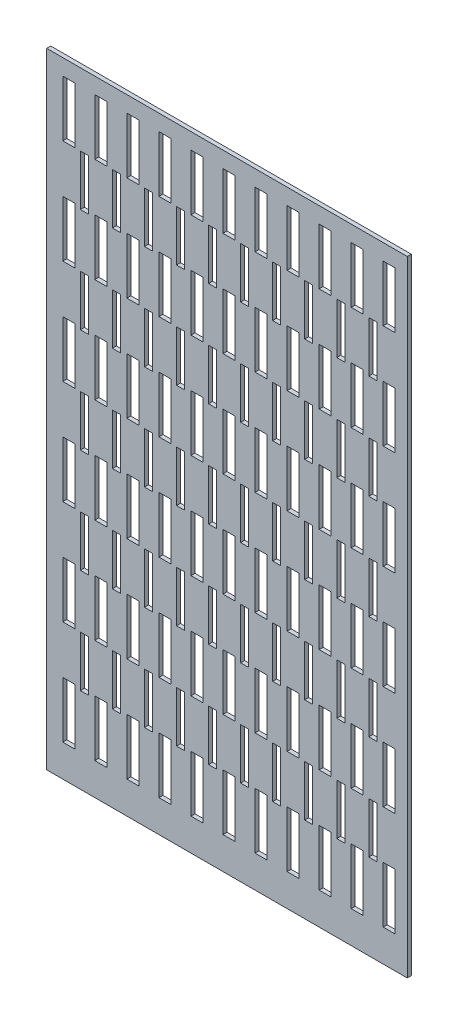
SolidWorks part; units mm, degrees
ref_plane "前视基准面" through (0, 0, 0) normal (0, 0, 1) x (1, 0, 0)
ref_plane "上视基准面" through (0, 0, 0) normal (0, 1, 0) x (1, 0, 0)
ref_plane "右视基准面" through (0, 0, 0) normal (1, 0, 0) x (0, 0, -1)
sketch "草图1" plane through (0, 0, 0) normal (0, 0, 1) x (1, 0, 0)
  line L1 (-22.5, 78) -> (22.5, 78)
  line L2 (-22.5, 78) -> (-22.5, 0)
  line L3 (-22.5, 0) -> (22.5, 0)
  line L4 (22.5, 78) -> (22.5, 0)
  dimension "D1" = 45
  dimension "D2" = 78
  dimension "D3" = 22.5
extrude "凸台-拉伸1" add sketch "草图1" along normal blind 0.5
sketch "草图2" plane through (0, 0, 0.5) normal (0, 0, 1) x (1, 0, 0)
  line L0 (-22.5, 78) -> (-22.5, 0) construction
  line L1 (-20.5, 76) -> (-19, 76)
  line L2 (-20.5, 76) -> (-20.5, 69)
  line L3 (-20.5, 69) -> (-19, 69)
  line L4 (-19, 76) -> (-19, 69)
  line L5 (22.5, 78) -> (-22.5, 78) construction
  line L6 (-16.5, 76) -> (-16.5, 69)
  line L7 (-16.5, 76) -> (-15, 76)
  line L8 (-15, 76) -> (-15, 69)
  line L9 (-16.5, 69) -> (-15, 69)
  line L10 (-12.5, 76) -> (-12.5, 69)
  line L11 (-12.5, 76) -> (-11, 76)
  line L12 (-11, 76) -> (-11, 69)
  line L13 (-12.5, 69) -> (-11, 69)
  line L14 (-8.5, 76) -> (-8.5, 69)
  line L15 (-8.5, 76) -> (-7, 76)
  line L16 (-7, 76) -> (-7, 69)
  line L17 (-8.5, 69) -> (-7, 69)
  line L18 (-4.5, 76) -> (-4.5, 69)
  line L19 (-4.5, 76) -> (-3, 76)
  line L20 (-3, 76) -> (-3, 69)
  line L21 (-4.5, 69) -> (-3, 69)
  line L22 (-0.5, 76) -> (-0.5, 69)
  line L23 (-0.5, 76) -> (1, 76)
  line L24 (1, 76) -> (1, 69)
  line L25 (-0.5, 69) -> (1, 69)
  line L26 (3.5, 76) -> (3.5, 69)
  line L27 (3.5, 76) -> (5, 76)
  line L28 (5, 76) -> (5, 69)
  line L29 (3.5, 69) -> (5, 69)
  line L30 (7.5, 76) -> (7.5, 69)
  line L31 (7.5, 76) -> (9, 76)
  line L32 (9, 76) -> (9, 69)
  line L33 (7.5, 69) -> (9, 69)
  line L34 (11.5, 76) -> (11.5, 69)
  line L35 (11.5, 76) -> (13, 76)
  line L36 (13, 76) -> (13, 69)
  line L37 (11.5, 69) -> (13, 69)
  line L38 (15.5, 76) -> (15.5, 69)
  line L39 (15.5, 76) -> (17, 76)
  line L40 (17, 76) -> (17, 69)
  line L41 (15.5, 69) -> (17, 69)
  line L42 (19.5, 76) -> (19.5, 69)
  line L43 (19.5, 76) -> (21, 76)
  line L44 (21, 76) -> (21, 69)
  line L45 (19.5, 69) -> (21, 69)
  line L46 (-20.5, 63) -> (-20.5, 56)
  line L47 (-20.5, 63) -> (-19, 63)
  line L48 (-19, 63) -> (-19, 56)
  line L49 (-20.5, 56) -> (-19, 56)
  line L50 (-16.5, 63) -> (-16.5, 56)
  line L51 (-16.5, 56) -> (-15, 56)
  line L52 (-15, 63) -> (-15, 56)
  line L53 (-16.5, 63) -> (-15, 63)
  line L54 (-12.5, 63) -> (-12.5, 56)
  line L55 (-12.5, 56) -> (-11, 56)
  line L56 (-11, 63) -> (-11, 56)
  line L57 (-12.5, 63) -> (-11, 63)
  line L58 (-8.5, 63) -> (-8.5, 56)
  line L59 (-8.5, 56) -> (-7, 56)
  line L60 (-7, 63) -> (-7, 56)
  line L61 (-8.5, 63) -> (-7, 63)
  line L62 (-4.5, 63) -> (-4.5, 56)
  line L63 (-4.5, 56) -> (-3, 56)
  line L64 (-3, 63) -> (-3, 56)
  line L65 (-4.5, 63) -> (-3, 63)
  line L66 (-0.5, 63) -> (-0.5, 56)
  line L67 (-0.5, 56) -> (1, 56)
  line L68 (1, 63) -> (1, 56)
  line L69 (-0.5, 63) -> (1, 63)
  line L70 (3.5, 63) -> (3.5, 56)
  line L71 (3.5, 56) -> (5, 56)
  line L72 (5, 63) -> (5, 56)
  line L73 (3.5, 63) -> (5, 63)
  line L74 (7.5, 63) -> (7.5, 56)
  line L75 (7.5, 56) -> (9, 56)
  line L76 (9, 63) -> (9, 56)
  line L77 (7.5, 63) -> (9, 63)
  line L78 (11.5, 63) -> (11.5, 56)
  line L79 (11.5, 56) -> (13, 56)
  line L80 (13, 63) -> (13, 56)
  line L81 (11.5, 63) -> (13, 63)
  line L82 (15.5, 63) -> (15.5, 56)
  line L83 (15.5, 56) -> (17, 56)
  line L84 (17, 63) -> (17, 56)
  line L85 (15.5, 63) -> (17, 63)
  line L86 (19.5, 63) -> (19.5, 56)
  line L87 (19.5, 56) -> (21, 56)
  line L88 (21, 63) -> (21, 56)
  line L89 (19.5, 63) -> (21, 63)
  line L90 (-20.5, 50) -> (-20.5, 43)
  line L91 (-20.5, 50) -> (-19, 50)
  line L92 (-19, 50) -> (-19, 43)
  line L93 (-20.5, 43) -> (-19, 43)
  line L94 (-16.5, 50) -> (-16.5, 43)
  line L95 (-16.5, 43) -> (-15, 43)
  line L96 (-15, 50) -> (-15, 43)
  line L97 (-16.5, 50) -> (-15, 50)
  line L98 (-12.5, 50) -> (-12.5, 43)
  line L99 (-12.5, 43) -> (-11, 43)
  line L100 (-11, 50) -> (-11, 43)
  line L101 (-12.5, 50) -> (-11, 50)
  line L102 (-8.5, 50) -> (-8.5, 43)
  line L103 (-8.5, 43) -> (-7, 43)
  line L104 (-7, 50) -> (-7, 43)
  line L105 (-8.5, 50) -> (-7, 50)
  line L106 (-4.5, 50) -> (-4.5, 43)
  line L107 (-4.5, 43) -> (-3, 43)
  line L108 (-3, 50) -> (-3, 43)
  line L109 (-4.5, 50) -> (-3, 50)
  line L110 (-0.5, 50) -> (-0.5, 43)
  line L111 (-0.5, 43) -> (1, 43)
  line L112 (1, 50) -> (1, 43)
  line L113 (-0.5, 50) -> (1, 50)
  line L114 (3.5, 50) -> (3.5, 43)
  line L115 (3.5, 43) -> (5, 43)
  line L116 (5, 50) -> (5, 43)
  line L117 (3.5, 50) -> (5, 50)
  line L118 (7.5, 50) -> (7.5, 43)
  line L119 (7.5, 43) -> (9, 43)
  line L120 (9, 50) -> (9, 43)
  line L121 (7.5, 50) -> (9, 50)
  line L122 (11.5, 50) -> (11.5, 43)
  line L123 (11.5, 43) -> (13, 43)
  line L124 (13, 50) -> (13, 43)
  line L125 (11.5, 50) -> (13, 50)
  line L126 (15.5, 50) -> (15.5, 43)
  line L127 (15.5, 43) -> (17, 43)
  line L128 (17, 50) -> (17, 43)
  line L129 (15.5, 50) -> (17, 50)
  line L130 (19.5, 50) -> (19.5, 43)
  line L131 (19.5, 43) -> (21, 43)
  line L132 (21, 50) -> (21, 43)
  line L133 (19.5, 50) -> (21, 50)
  line L134 (-20.5, 37) -> (-20.5, 30)
  line L135 (-20.5, 37) -> (-19, 37)
  line L136 (-19, 37) -> (-19, 30)
  line L137 (-20.5, 30) -> (-19, 30)
  line L138 (-16.5, 37) -> (-16.5, 30)
  line L139 (-16.5, 30) -> (-15, 30)
  line L140 (-15, 37) -> (-15, 30)
  line L141 (-16.5, 37) -> (-15, 37)
  line L142 (-12.5, 37) -> (-12.5, 30)
  line L143 (-12.5, 30) -> (-11, 30)
  line L144 (-11, 37) -> (-11, 30)
  line L145 (-12.5, 37) -> (-11, 37)
  line L146 (-8.5, 37) -> (-8.5, 30)
  line L147 (-8.5, 30) -> (-7, 30)
  line L148 (-7, 37) -> (-7, 30)
  line L149 (-8.5, 37) -> (-7, 37)
  line L150 (-4.5, 37) -> (-4.5, 30)
  line L151 (-4.5, 30) -> (-3, 30)
  line L152 (-3, 37) -> (-3, 30)
  line L153 (-4.5, 37) -> (-3, 37)
  line L154 (-0.5, 37) -> (-0.5, 30)
  line L155 (-0.5, 30) -> (1, 30)
  line L156 (1, 37) -> (1, 30)
  line L157 (-0.5, 37) -> (1, 37)
  line L158 (3.5, 37) -> (3.5, 30)
  line L159 (3.5, 30) -> (5, 30)
  line L160 (5, 37) -> (5, 30)
  line L161 (3.5, 37) -> (5, 37)
  line L162 (7.5, 37) -> (7.5, 30)
  line L163 (7.5, 30) -> (9, 30)
  line L164 (9, 37) -> (9, 30)
  line L165 (7.5, 37) -> (9, 37)
  line L166 (11.5, 37) -> (11.5, 30)
  line L167 (11.5, 30) -> (13, 30)
  line L168 (13, 37) -> (13, 30)
  line L169 (11.5, 37) -> (13, 37)
  line L170 (15.5, 37) -> (15.5, 30)
  line L171 (15.5, 30) -> (17, 30)
  line L172 (17, 37) -> (17, 30)
  line L173 (15.5, 37) -> (17, 37)
  line L174 (19.5, 37) -> (19.5, 30)
  line L175 (19.5, 30) -> (21, 30)
  line L176 (21, 37) -> (21, 30)
  line L177 (19.5, 37) -> (21, 37)
  line L178 (-20.5, 24) -> (-20.5, 17)
  line L179 (-20.5, 24) -> (-19, 24)
  line L180 (-19, 24) -> (-19, 17)
  line L181 (-20.5, 17) -> (-19, 17)
  line L182 (-16.5, 24) -> (-16.5, 17)
  line L183 (-16.5, 17) -> (-15, 17)
  line L184 (-15, 24) -> (-15, 17)
  line L185 (-16.5, 24) -> (-15, 24)
  line L186 (-12.5, 24) -> (-12.5, 17)
  line L187 (-12.5, 17) -> (-11, 17)
  line L188 (-11, 24) -> (-11, 17)
  line L189 (-12.5, 24) -> (-11, 24)
  line L190 (-8.5, 24) -> (-8.5, 17)
  line L191 (-8.5, 17) -> (-7, 17)
  line L192 (-7, 24) -> (-7, 17)
  line L193 (-8.5, 24) -> (-7, 24)
  line L194 (-4.5, 24) -> (-4.5, 17)
  line L195 (-4.5, 17) -> (-3, 17)
  line L196 (-3, 24) -> (-3, 17)
  line L197 (-4.5, 24) -> (-3, 24)
  line L198 (-0.5, 24) -> (-0.5, 17)
  line L199 (-0.5, 17) -> (1, 17)
  line L200 (1, 24) -> (1, 17)
  line L201 (-0.5, 24) -> (1, 24)
  line L202 (3.5, 24) -> (3.5, 17)
  line L203 (3.5, 17) -> (5, 17)
  line L204 (5, 24) -> (5, 17)
  line L205 (3.5, 24) -> (5, 24)
  line L206 (7.5, 24) -> (7.5, 17)
  line L207 (7.5, 17) -> (9, 17)
  line L208 (9, 24) -> (9, 17)
  line L209 (7.5, 24) -> (9, 24)
  line L210 (11.5, 24) -> (11.5, 17)
  line L211 (11.5, 17) -> (13, 17)
  line L212 (13, 24) -> (13, 17)
  line L213 (11.5, 24) -> (13, 24)
  line L214 (15.5, 24) -> (15.5, 17)
  line L215 (15.5, 17) -> (17, 17)
  line L216 (17, 24) -> (17, 17)
  line L217 (15.5, 24) -> (17, 24)
  line L218 (19.5, 24) -> (19.5, 17)
  line L219 (19.5, 17) -> (21, 17)
  line L220 (21, 24) -> (21, 17)
  line L221 (19.5, 24) -> (21, 24)
  line L222 (-20.5, 11) -> (-20.5, 4)
  line L223 (-20.5, 11) -> (-19, 11)
  line L224 (-19, 11) -> (-19, 4)
  line L225 (-20.5, 4) -> (-19, 4)
  line L226 (-16.5, 11) -> (-16.5, 4)
  line L227 (-16.5, 4) -> (-15, 4)
  line L228 (-15, 11) -> (-15, 4)
  line L229 (-16.5, 11) -> (-15, 11)
  line L230 (-12.5, 11) -> (-12.5, 4)
  line L231 (-12.5, 4) -> (-11, 4)
  line L232 (-11, 11) -> (-11, 4)
  line L233 (-12.5, 11) -> (-11, 11)
  line L234 (-8.5, 11) -> (-8.5, 4)
  line L235 (-8.5, 4) -> (-7, 4)
  line L236 (-7, 11) -> (-7, 4)
  line L237 (-8.5, 11) -> (-7, 11)
  line L238 (-4.5, 11) -> (-4.5, 4)
  line L239 (-4.5, 4) -> (-3, 4)
  line L240 (-3, 11) -> (-3, 4)
  line L241 (-4.5, 11) -> (-3, 11)
  line L242 (-0.5, 11) -> (-0.5, 4)
  line L243 (-0.5, 4) -> (1, 4)
  line L244 (1, 11) -> (1, 4)
  line L245 (-0.5, 11) -> (1, 11)
  line L246 (3.5, 11) -> (3.5, 4)
  line L247 (3.5, 4) -> (5, 4)
  line L248 (5, 11) -> (5, 4)
  line L249 (3.5, 11) -> (5, 11)
  line L250 (7.5, 11) -> (7.5, 4)
  line L251 (7.5, 4) -> (9, 4)
  line L252 (9, 11) -> (9, 4)
  line L253 (7.5, 11) -> (9, 11)
  line L254 (11.5, 11) -> (11.5, 4)
  line L255 (11.5, 4) -> (13, 4)
  line L256 (13, 11) -> (13, 4)
  line L257 (11.5, 11) -> (13, 11)
  line L258 (15.5, 11) -> (15.5, 4)
  line L259 (15.5, 4) -> (17, 4)
  line L260 (17, 11) -> (17, 4)
  line L261 (15.5, 11) -> (17, 11)
  line L262 (19.5, 11) -> (19.5, 4)
  line L263 (19.5, 4) -> (21, 4)
  line L264 (21, 11) -> (21, 4)
  line L265 (19.5, 11) -> (21, 11)
  line L266 (-14.3, 69) -> (-14.3, 62.6737)
  line L267 (-18.3, 69) -> (-17.3, 69)
  line L268 (-18.3, 69) -> (-18.3, 62.6737)
  line L269 (-18.3, 62.6737) -> (-17.3, 62.6737)
  line L270 (-17.3, 69) -> (-17.3, 62.6737)
  line L271 (-14.3, 69) -> (-13.3, 69)
  line L272 (-13.3, 69) -> (-13.3, 62.6737)
  line L273 (-14.3, 62.6737) -> (-13.3, 62.6737)
  line L274 (-10.3, 69) -> (-10.3, 62.6737)
  line L275 (-10.3, 69) -> (-9.3, 69)
  line L276 (-9.3, 69) -> (-9.3, 62.6737)
  line L277 (-10.3, 62.6737) -> (-9.3, 62.6737)
  line L278 (-6.3, 69) -> (-6.3, 62.6737)
  line L279 (-6.3, 69) -> (-5.3, 69)
  line L280 (-5.3, 69) -> (-5.3, 62.6737)
  line L281 (-6.3, 62.6737) -> (-5.3, 62.6737)
  line L282 (-2.3, 69) -> (-2.3, 62.6737)
  line L283 (-2.3, 69) -> (-1.3, 69)
  line L284 (-1.3, 69) -> (-1.3, 62.6737)
  line L285 (-2.3, 62.6737) -> (-1.3, 62.6737)
  line L286 (1.7, 69) -> (1.7, 62.6737)
  line L287 (1.7, 69) -> (2.7, 69)
  line L288 (2.7, 69) -> (2.7, 62.6737)
  line L289 (1.7, 62.6737) -> (2.7, 62.6737)
  line L290 (5.7, 69) -> (5.7, 62.6737)
  line L291 (5.7, 69) -> (6.7, 69)
  line L292 (6.7, 69) -> (6.7, 62.6737)
  line L293 (5.7, 62.6737) -> (6.7, 62.6737)
  line L294 (9.7, 69) -> (9.7, 62.6737)
  line L295 (9.7, 69) -> (10.7, 69)
  line L296 (10.7, 69) -> (10.7, 62.6737)
  line L297 (9.7, 62.6737) -> (10.7, 62.6737)
  line L298 (13.7, 69) -> (13.7, 62.6737)
  line L299 (13.7, 69) -> (14.7, 69)
  line L300 (14.7, 69) -> (14.7, 62.6737)
  line L301 (13.7, 62.6737) -> (14.7, 62.6737)
  line L302 (17.7, 69) -> (17.7, 62.6737)
  line L303 (17.7, 69) -> (18.7, 69)
  line L304 (18.7, 69) -> (18.7, 62.6737)
  line L305 (17.7, 62.6737) -> (18.7, 62.6737)
  line L306 (-18.3, 56) -> (-18.3, 49.6737)
  line L307 (-18.3, 56) -> (-17.3, 56)
  line L308 (-17.3, 56) -> (-17.3, 49.6737)
  line L309 (-18.3, 49.6737) -> (-17.3, 49.6737)
  line L310 (-14.3, 56) -> (-14.3, 49.6737)
  line L311 (-14.3, 49.6737) -> (-13.3, 49.6737)
  line L312 (-13.3, 56) -> (-13.3, 49.6737)
  line L313 (-14.3, 56) -> (-13.3, 56)
  line L314 (-10.3, 56) -> (-10.3, 49.6737)
  line L315 (-10.3, 49.6737) -> (-9.3, 49.6737)
  line L316 (-9.3, 56) -> (-9.3, 49.6737)
  line L317 (-10.3, 56) -> (-9.3, 56)
  line L318 (-6.3, 56) -> (-6.3, 49.6737)
  line L319 (-6.3, 49.6737) -> (-5.3, 49.6737)
  line L320 (-5.3, 56) -> (-5.3, 49.6737)
  line L321 (-6.3, 56) -> (-5.3, 56)
  line L322 (-2.3, 56) -> (-2.3, 49.6737)
  line L323 (-2.3, 49.6737) -> (-1.3, 49.6737)
  line L324 (-1.3, 56) -> (-1.3, 49.6737)
  line L325 (-2.3, 56) -> (-1.3, 56)
  line L326 (1.7, 56) -> (1.7, 49.6737)
  line L327 (1.7, 49.6737) -> (2.7, 49.6737)
  line L328 (2.7, 56) -> (2.7, 49.6737)
  line L329 (1.7, 56) -> (2.7, 56)
  line L330 (5.7, 56) -> (5.7, 49.6737)
  line L331 (5.7, 49.6737) -> (6.7, 49.6737)
  line L332 (6.7, 56) -> (6.7, 49.6737)
  line L333 (5.7, 56) -> (6.7, 56)
  line L334 (9.7, 56) -> (9.7, 49.6737)
  line L335 (9.7, 49.6737) -> (10.7, 49.6737)
  line L336 (10.7, 56) -> (10.7, 49.6737)
  line L337 (9.7, 56) -> (10.7, 56)
  line L338 (13.7, 56) -> (13.7, 49.6737)
  line L339 (13.7, 49.6737) -> (14.7, 49.6737)
  line L340 (14.7, 56) -> (14.7, 49.6737)
  line L341 (13.7, 56) -> (14.7, 56)
  line L342 (17.7, 56) -> (17.7, 49.6737)
  line L343 (17.7, 49.6737) -> (18.7, 49.6737)
  line L344 (18.7, 56) -> (18.7, 49.6737)
  line L345 (17.7, 56) -> (18.7, 56)
  line L346 (-18.3, 43) -> (-18.3, 36.6737)
  line L347 (-18.3, 43) -> (-17.3, 43)
  line L348 (-17.3, 43) -> (-17.3, 36.6737)
  line L349 (-18.3, 36.6737) -> (-17.3, 36.6737)
  line L350 (-14.3, 43) -> (-14.3, 36.6737)
  line L351 (-14.3, 36.6737) -> (-13.3, 36.6737)
  line L352 (-13.3, 43) -> (-13.3, 36.6737)
  line L353 (-14.3, 43) -> (-13.3, 43)
  line L354 (-10.3, 43) -> (-10.3, 36.6737)
  line L355 (-10.3, 36.6737) -> (-9.3, 36.6737)
  line L356 (-9.3, 43) -> (-9.3, 36.6737)
  line L357 (-10.3, 43) -> (-9.3, 43)
  line L358 (-6.3, 43) -> (-6.3, 36.6737)
  line L359 (-6.3, 36.6737) -> (-5.3, 36.6737)
  line L360 (-5.3, 43) -> (-5.3, 36.6737)
  line L361 (-6.3, 43) -> (-5.3, 43)
  line L362 (-2.3, 43) -> (-2.3, 36.6737)
  line L363 (-2.3, 36.6737) -> (-1.3, 36.6737)
  line L364 (-1.3, 43) -> (-1.3, 36.6737)
  line L365 (-2.3, 43) -> (-1.3, 43)
  line L366 (1.7, 43) -> (1.7, 36.6737)
  line L367 (1.7, 36.6737) -> (2.7, 36.6737)
  line L368 (2.7, 43) -> (2.7, 36.6737)
  line L369 (1.7, 43) -> (2.7, 43)
  line L370 (5.7, 43) -> (5.7, 36.6737)
  line L371 (5.7, 36.6737) -> (6.7, 36.6737)
  line L372 (6.7, 43) -> (6.7, 36.6737)
  line L373 (5.7, 43) -> (6.7, 43)
  line L374 (9.7, 43) -> (9.7, 36.6737)
  line L375 (9.7, 36.6737) -> (10.7, 36.6737)
  line L376 (10.7, 43) -> (10.7, 36.6737)
  line L377 (9.7, 43) -> (10.7, 43)
  line L378 (13.7, 43) -> (13.7, 36.6737)
  line L379 (13.7, 36.6737) -> (14.7, 36.6737)
  line L380 (14.7, 43) -> (14.7, 36.6737)
  line L381 (13.7, 43) -> (14.7, 43)
  line L382 (17.7, 43) -> (17.7, 36.6737)
  line L383 (17.7, 36.6737) -> (18.7, 36.6737)
  line L384 (18.7, 43) -> (18.7, 36.6737)
  line L385 (17.7, 43) -> (18.7, 43)
  line L386 (-18.3, 30) -> (-18.3, 23.6737)
  line L387 (-18.3, 30) -> (-17.3, 30)
  line L388 (-17.3, 30) -> (-17.3, 23.6737)
  line L389 (-18.3, 23.6737) -> (-17.3, 23.6737)
  line L390 (-14.3, 30) -> (-14.3, 23.6737)
  line L391 (-14.3, 23.6737) -> (-13.3, 23.6737)
  line L392 (-13.3, 30) -> (-13.3, 23.6737)
  line L393 (-14.3, 30) -> (-13.3, 30)
  line L394 (-10.3, 30) -> (-10.3, 23.6737)
  line L395 (-10.3, 23.6737) -> (-9.3, 23.6737)
  line L396 (-9.3, 30) -> (-9.3, 23.6737)
  line L397 (-10.3, 30) -> (-9.3, 30)
  line L398 (-6.3, 30) -> (-6.3, 23.6737)
  line L399 (-6.3, 23.6737) -> (-5.3, 23.6737)
  line L400 (-5.3, 30) -> (-5.3, 23.6737)
  line L401 (-6.3, 30) -> (-5.3, 30)
  line L402 (-2.3, 30) -> (-2.3, 23.6737)
  line L403 (-2.3, 23.6737) -> (-1.3, 23.6737)
  line L404 (-1.3, 30) -> (-1.3, 23.6737)
  line L405 (-2.3, 30) -> (-1.3, 30)
  line L406 (1.7, 30) -> (1.7, 23.6737)
  line L407 (1.7, 23.6737) -> (2.7, 23.6737)
  line L408 (2.7, 30) -> (2.7, 23.6737)
  line L409 (1.7, 30) -> (2.7, 30)
  line L410 (5.7, 30) -> (5.7, 23.6737)
  line L411 (5.7, 23.6737) -> (6.7, 23.6737)
  line L412 (6.7, 30) -> (6.7, 23.6737)
  line L413 (5.7, 30) -> (6.7, 30)
  line L414 (9.7, 30) -> (9.7, 23.6737)
  line L415 (9.7, 23.6737) -> (10.7, 23.6737)
  line L416 (10.7, 30) -> (10.7, 23.6737)
  line L417 (9.7, 30) -> (10.7, 30)
  line L418 (13.7, 30) -> (13.7, 23.6737)
  line L419 (13.7, 23.6737) -> (14.7, 23.6737)
  line L420 (14.7, 30) -> (14.7, 23.6737)
  line L421 (13.7, 30) -> (14.7, 30)
  line L422 (17.7, 30) -> (17.7, 23.6737)
  line L423 (17.7, 23.6737) -> (18.7, 23.6737)
  line L424 (18.7, 30) -> (18.7, 23.6737)
  line L425 (17.7, 30) -> (18.7, 30)
  line L426 (-18.3, 17) -> (-18.3, 10.6737)
  line L427 (-18.3, 17) -> (-17.3, 17)
  line L428 (-17.3, 17) -> (-17.3, 10.6737)
  line L429 (-18.3, 10.6737) -> (-17.3, 10.6737)
  line L430 (-14.3, 17) -> (-14.3, 10.6737)
  line L431 (-14.3, 10.6737) -> (-13.3, 10.6737)
  line L432 (-13.3, 17) -> (-13.3, 10.6737)
  line L433 (-14.3, 17) -> (-13.3, 17)
  line L434 (-10.3, 17) -> (-10.3, 10.6737)
  line L435 (-10.3, 10.6737) -> (-9.3, 10.6737)
  line L436 (-9.3, 17) -> (-9.3, 10.6737)
  line L437 (-10.3, 17) -> (-9.3, 17)
  line L438 (-6.3, 17) -> (-6.3, 10.6737)
  line L439 (-6.3, 10.6737) -> (-5.3, 10.6737)
  line L440 (-5.3, 17) -> (-5.3, 10.6737)
  line L441 (-6.3, 17) -> (-5.3, 17)
  line L442 (-2.3, 17) -> (-2.3, 10.6737)
  line L443 (-2.3, 10.6737) -> (-1.3, 10.6737)
  line L444 (-1.3, 17) -> (-1.3, 10.6737)
  line L445 (-2.3, 17) -> (-1.3, 17)
  line L446 (1.7, 17) -> (1.7, 10.6737)
  line L447 (1.7, 10.6737) -> (2.7, 10.6737)
  line L448 (2.7, 17) -> (2.7, 10.6737)
  line L449 (1.7, 17) -> (2.7, 17)
  line L450 (5.7, 17) -> (5.7, 10.6737)
  line L451 (5.7, 10.6737) -> (6.7, 10.6737)
  line L452 (6.7, 17) -> (6.7, 10.6737)
  line L453 (5.7, 17) -> (6.7, 17)
  line L454 (9.7, 17) -> (9.7, 10.6737)
  line L455 (9.7, 10.6737) -> (10.7, 10.6737)
  line L456 (10.7, 17) -> (10.7, 10.6737)
  line L457 (9.7, 17) -> (10.7, 17)
  line L458 (13.7, 17) -> (13.7, 10.6737)
  line L459 (13.7, 10.6737) -> (14.7, 10.6737)
  line L460 (14.7, 17) -> (14.7, 10.6737)
  line L461 (13.7, 17) -> (14.7, 17)
  line L462 (17.7, 17) -> (17.7, 10.6737)
  line L463 (17.7, 10.6737) -> (18.7, 10.6737)
  line L464 (18.7, 17) -> (18.7, 10.6737)
  line L465 (17.7, 17) -> (18.7, 17)
  dimension "D1" = 1.5
  dimension "D2" = 7
  dimension "D3" = 2
  dimension "D4" = 2
  dimension "D7" = 1
  dimension "D8" = 0.7
  dimension "D5" = 11
  dimension "D6" = 6
  dimension "D9" = 10
  dimension "D10" = 5
extrude "切除-拉伸1" cut sketch "草图2" against normal blind 0.5
